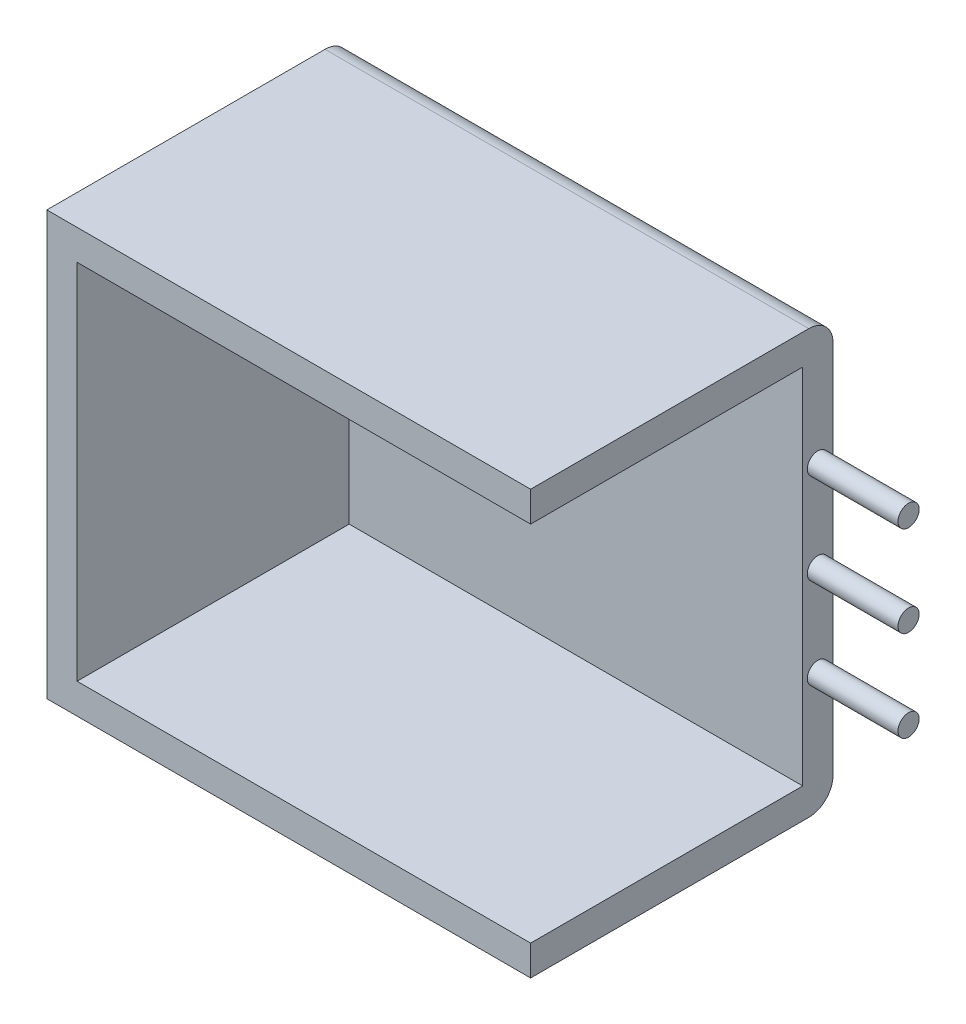
SolidWorks part; units mm, degrees
ref_plane "Front Plane" through (0, 0, 0) normal (0, 0, 1) x (1, 0, 0)
ref_plane "Top Plane" through (0, 0, 0) normal (0, 1, 0) x (1, 0, 0)
ref_plane "Right Plane" through (0, 0, 0) normal (1, 0, 0) x (0, 0, -1)
sketch "Sketch1" plane through (0, 0, 0) normal (0, 0, 1) x (1, 0, 0)
  line L1 (-150, -60) -> (0, -60)
  line L2 (-150, -60) -> (-150, 60)
  line L3 (-150, 60) -> (0, 60)
  line L4 (0, -60) -> (0, 60)
  line L5 (-150, -60) -> (0, 60) construction
  line L6 (-150, 60) -> (0, -60) construction
  point P0 (-75, 0)
  point P5 (0, 0)
  dimension "D1" = 150
  dimension "D2" = 120
extrude "Boss-Extrude1" add sketch "Sketch1" along normal blind 10
sketch "Sketch2" plane through (0, 0, 0) normal (1, 0, 0) x (0, 0, -1)
  line L1 (-10, -60) -> (-10, 60) construction
  circle A0 centre (-5, 30) radius 3.5
  circle A1 centre (-5, -30) radius 3.5
  circle A2 centre (-5, 0) radius 3.5
  dimension "D1" = 7
  dimension "D2" = 30
  dimension "D3" = 30
  dimension "D4" = 5
extrude "Boss-Extrude2" add sketch "Sketch2" along normal blind 30
sketch "Croquis2" plane through (-150, 0, 0) normal (-1, 0, 0) x (0, 0, 1)
  line L0 (0, 60) -> (0, -60)
  line L1 (0, 60) -> (100, 60)
  line L2 (0, -60) -> (100, -60)
  line L3 (100, 60) -> (100, -60)
  dimension "D1" = 100
extrude "Saliente-Extruir1" add sketch "Croquis2" along normal blind 10
sketch "Croquis3" plane through (0, -60, 0) normal (0, -1, 0) x (1, 0, 0)
  line L0 (-160, 0) -> (0, 0)
  line L1 (-160, 0) -> (-160, 100)
  line L2 (0, 0) -> (0, 100)
  line L3 (-160, 100) -> (0, 100)
  dimension "D1" = 100
extrude "Saliente-Extruir2" add sketch "Croquis3" along normal blind 10
sketch "Croquis4" plane through (0, 60, 0) normal (0, 1, 0) x (1, 0, 0)
  line L0 (-160, 0) -> (0, 0)
  line L1 (-160, 0) -> (-160, -100)
  line L2 (0, 0) -> (0, -100)
  line L3 (-160, -100) -> (0, -100)
  dimension "D1" = 100
extrude "Saliente-Extruir3" add sketch "Croquis4" along normal blind 10
fillet "Fillet1" radius 8 2 edges at (-80, -70, 0) (-80, 70, 0)
